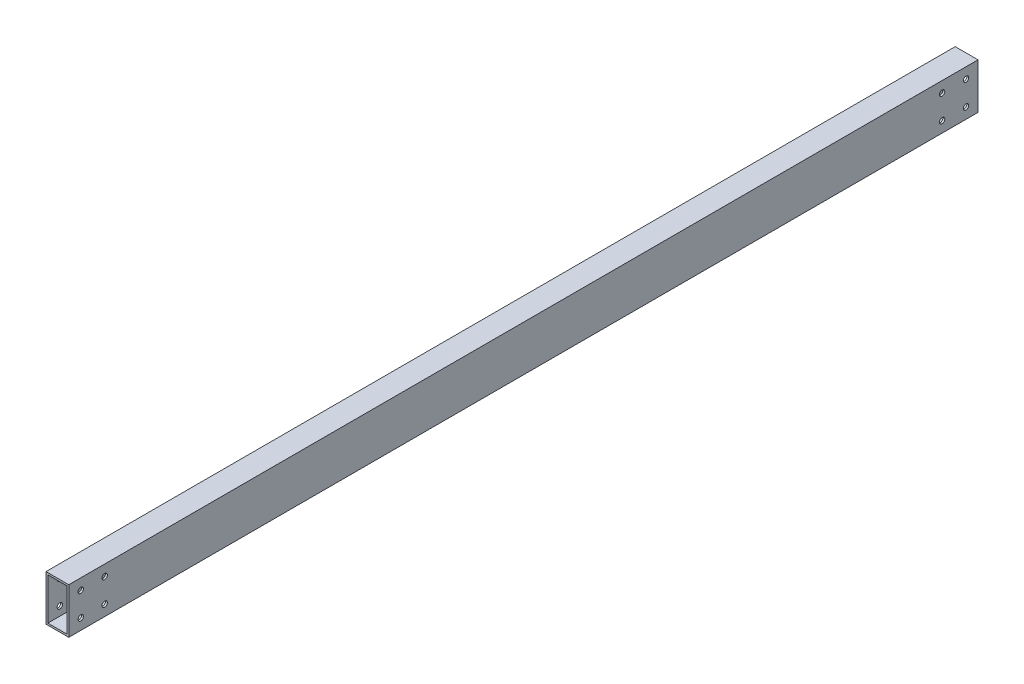
SolidWorks part; units mm, degrees
material "6063-T6"
ref_plane "Front Plane" through (0, 0, 0) normal (0, 0, 1) x (1, 0, 0)
ref_plane "Top Plane" through (0, 0, 0) normal (0, 1, 0) x (1, 0, 0)
ref_plane "Right Plane" through (0, 0, 0) normal (1, 0, 0) x (0, 0, -1)
sketch "Sketch1" plane through (0, 0, 0) normal (0, 0, 1) x (1, 0, 0)
  line L1 (-19.05, 38.1) -> (19.05, 38.1)
  line L2 (-19.05, 38.1) -> (-19.05, -38.1)
  line L3 (-19.05, -38.1) -> (19.05, -38.1)
  line L4 (19.05, 38.1) -> (19.05, -38.1)
  line L5 (-19.05, 38.1) -> (19.05, -38.1) construction
  line L6 (-19.05, -38.1) -> (19.05, 38.1) construction
  point P0 (0, 0)
  dimension "D1" = 38.1
  dimension "D2" = 76.2
extrude "Extrude-Thin1" add sketch "Sketch1" along normal mid plane 1520 thin
hole_wizard "M8 Clearance Hole2" positions "Sketch5" profile "Sketch6" hole size "M8" standard "ANSI Metric"
sketch "Sketch5" plane through (19.05, 0, 0) normal (1, 0, 0) x (0, 0, -1)
  line L0 (-740, 20) -> (-740, -20)
  line L2 (20.955, 0) -> (-20.955, 0) construction
  line L3 (-760, -38.1) -> (-760, 38.1) construction
  line L4 (-740, 20) -> (-700, 20)
  line L5 (-700, 20) -> (-700, -20)
  line L6 (-700, -20) -> (-740, -20)
  point P0 (-740, 20)
  point P2 (-740, -20)
  point P9 (-740, 0)
  point P24 (-700, 20)
  point P27 (-700, -20)
  dimension "D1" = 40
  dimension "D2" = 20
sketch "Sketch6" plane through (19.05, 20, 740) normal (0, 1, 0) x (0, 0, -1)
  line L0 (0, 0) -> (0, 3.175)
  line L1 (0, 3.175) -> (4.5, 3.175)
  line L2 (4.5, 3.175) -> (4.5, 0)
  line L5 (4.5, 0) -> (0, 0)
  line L11 (0, -6.35) -> (0, 107.95) construction
  dimension "Thru Hole Dia." = 9
  dimension "Thru Hole Depth" = 3.175
hole_wizard "M8 Clearance Hole1" positions "Sketch7" profile "Sketch8" hole size "M8" standard "ANSI Metric" end condition up to next
sketch "Sketch7" plane through (-15.875, 0, 0) normal (1, 0, 0) x (0, 0, -1)
  point P0 (-740, 20)
  point P3 (-740, -20)
  point P6 (-700, 20)
  point P9 (-700, -20)
sketch "Sketch8" plane through (-15.875, 20, 740) normal (0, 1, 0) x (0, 0, -1)
  line L0 (0, 0) -> (0, 3.175)
  line L1 (0, 3.175) -> (4.5, 3.175)
  line L2 (4.5, 3.175) -> (4.5, 0)
  line L5 (4.5, 0) -> (0, 0)
  line L11 (0, -6.35) -> (0, 107.95) construction
  dimension "Thru Hole Dia." = 9
  dimension "Thru Hole Depth" = 3.175
mirror "Mirror1" about plane through (0, 0, 0) normal (0, 0, 1) of "M8 Clearance Hole2", "M8 Clearance Hole1"
